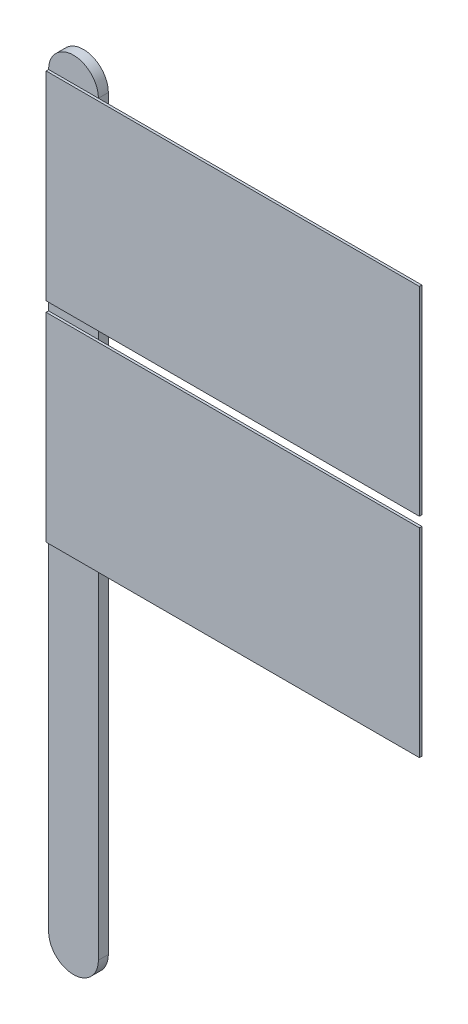
SolidWorks part; units mm, degrees
ref_plane "Front" through (0, 0, 0) normal (0, 0, 1) x (1, 0, 0)
ref_plane "Top" through (0, 0, 0) normal (0, 1, 0) x (1, 0, 0)
ref_plane "Right" through (0, 0, 0) normal (1, 0, 0) x (0, 0, -1)
sketch "Esquisse1" plane through (0, 0, 0) normal (0, 0, 1) x (1, 0, 0)
  line L0 (0, 0) -> (0, 150) construction
  line L1 (-5, 0) -> (-5, 150)
  line L2 (5, 0) -> (5, 150)
  arc A0 (-5, 0) -> (5, 0) centre (0, 0) ccw
  arc A1 (5, 150) -> (-5, 150) centre (0, 150) ccw
  point P3 (0, 75)
  dimension "D1" = 10
  dimension "D2" = 150
extrude "Boss.-Extru.1" add sketch "Esquisse1" along normal blind 2
sketch "Esquisse2" plane through (0, 0, 2) normal (0, 0, 1) x (1, 0, 0)
  line L0 (-5, 150) -> (-5, 0) construction
  line L1 (-5, 150) -> (70, 150)
  line L2 (-5, 150) -> (-5, 110)
  line L3 (-5, 110) -> (70, 110)
  line L4 (70, 150) -> (70, 110)
  line L5 (-5, 108) -> (70, 108)
  line L6 (-5, 108) -> (-5, 68)
  line L7 (-5, 68) -> (70, 68)
  line L8 (70, 108) -> (70, 68)
  dimension "D1" = 2
  dimension "D2" = 75
  dimension "D3" = 40
  dimension "D4" = 82
extrude "Boss.-Extru.2" add sketch "Esquisse2" along normal blind 0.5
equation "\"D3@Esquisse2\"=3000/\"D2@Esquisse2\""
